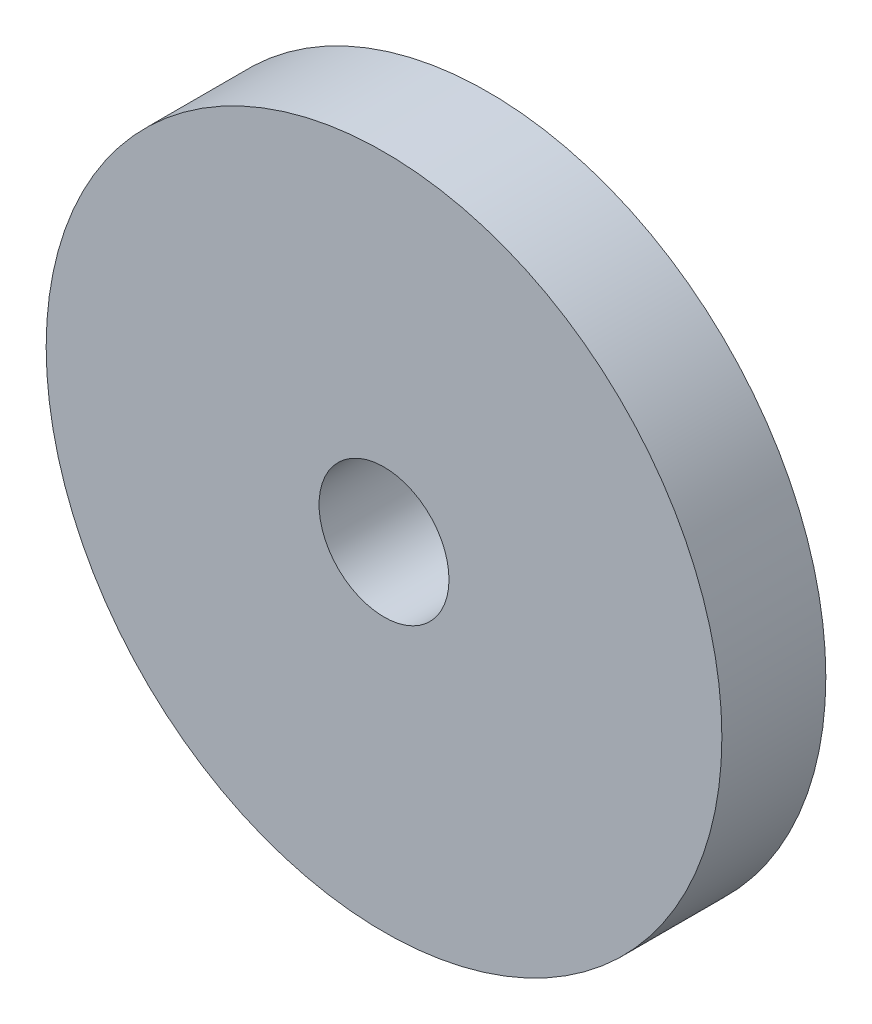
SolidWorks part; units mm, degrees
ref_plane "前视基准面" through (0, 0, 0) normal (0, 0, 1) x (1, 0, 0)
ref_plane "上视基准面" through (0, 0, 0) normal (0, 1, 0) x (1, 0, 0)
ref_plane "右视基准面" through (0, 0, 0) normal (1, 0, 0) x (0, 0, -1)
other "Configuration Table"
sketch "草图8" plane through (0, 0, 0) normal (0, 0, 1) x (1, 0, 0)
  circle A0 centre (0, 0) radius 130
  circle A1 centre (0, 0) radius 25
extrude "凸台-拉伸1" add sketch "草图8" along normal blind 40
